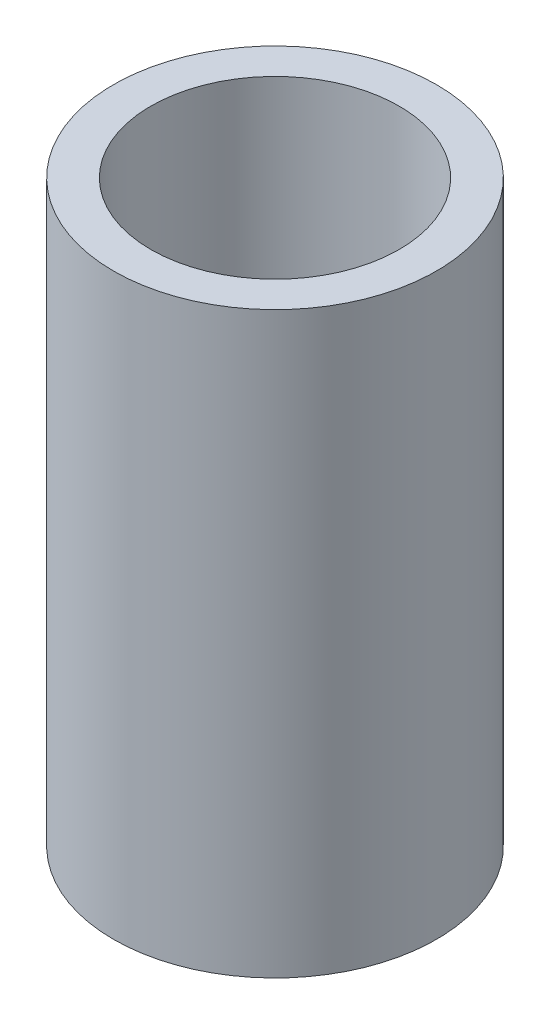
SolidWorks part; units mm, degrees
ref_plane "Front" through (0, 0, 0) normal (0, 0, 1) x (1, 0, 0)
ref_plane "Top" through (0, 0, 0) normal (0, 1, 0) x (1, 0, 0)
ref_plane "Right" through (0, 0, 0) normal (1, 0, 0) x (0, 0, -1)
sketch "Sketch1" plane through (0, 0, 0) normal (0, 1, 0) x (1, 0, 0)
  circle A0 centre (0, 0) radius 6.5
  circle A1 centre (0, 0) radius 5
  dimension "D1" = 10
  dimension "D2" = 1.5
extrude "Boss-Extrude1" add sketch "Sketch1" along normal blind 23.3
